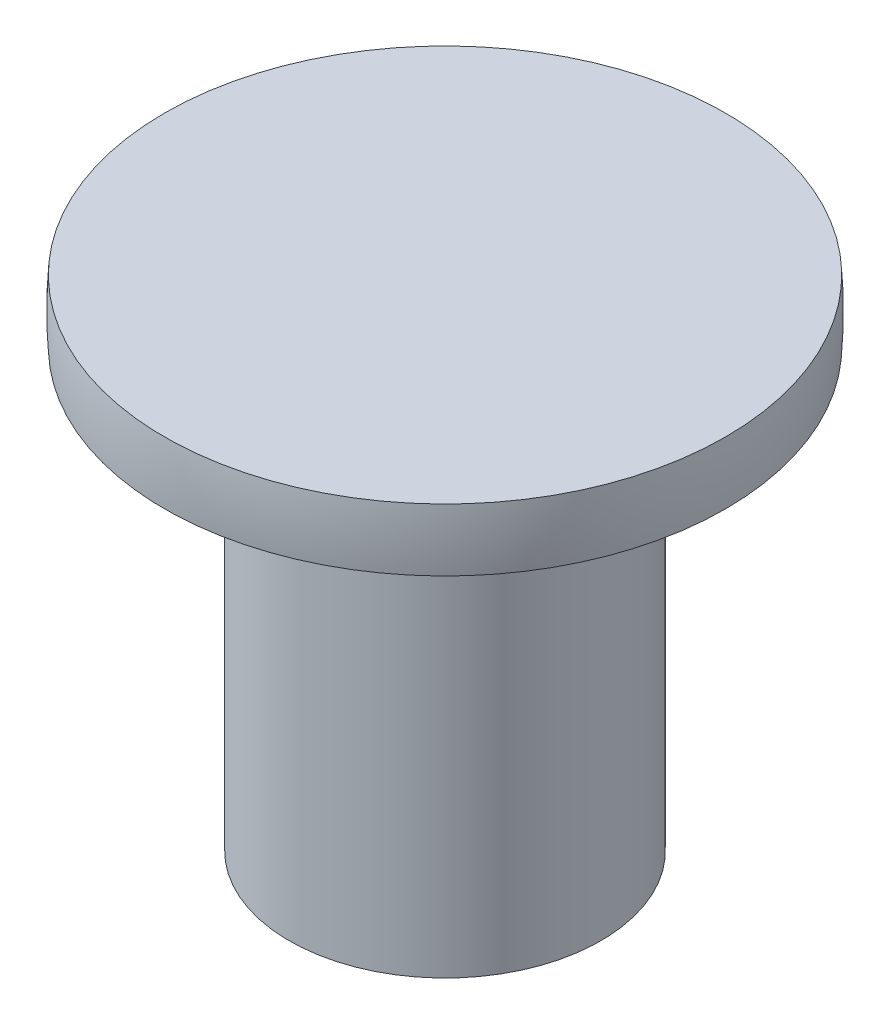
SolidWorks part; units mm, degrees
ref_plane "Front Plane" through (0, 0, 0) normal (0, 0, 1) x (1, 0, 0)
ref_plane "Top Plane" through (0, 0, 0) normal (0, 1, 0) x (1, 0, 0)
ref_plane "Right Plane" through (0, 0, 0) normal (1, 0, 0) x (0, 0, -1)
sketch "Sketch1" plane through (0, 0, 0) normal (0, 0, 1) x (1, 0, 0)
  line L0 (0, 8) -> (0, 4.5)
  line L1 (0, 4.5) -> (1.8, 4.5)
  line L2 (1.8, 4.5) -> (1.8, 0)
  line L3 (1.8, 0) -> (2.5, 0)
  line L4 (2.5, 0) -> (2.5, 7)
  line L5 (2.5, 7) -> (4.5, 7)
  line L7 (4.5, 8) -> (0, 8)
  line L8 (4.5, 8) -> (4.5, 7) construction
  line L9 (4.5192, 7.5) -> (-1.9859, 7.5) construction
  arc A0 (4.5, 7) -> (4.5, 8) centre (-1.9859, 7.5) ccw
  dimension "D1" = 2.5
  dimension "D2" = 1.8
  dimension "D3" = 8
  dimension "D4" = 3.5
  dimension "D5" = 1
  dimension "D6" = 4.5
revolve "Revolve1" add sketch "Sketch1" angle 360 about L0
